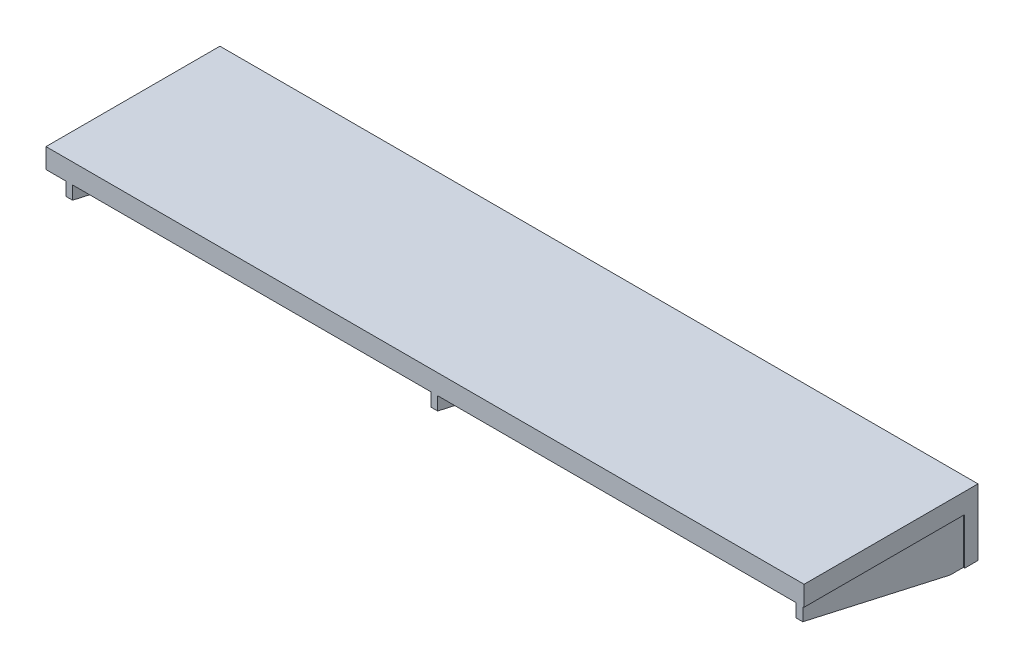
SolidWorks part; units mm, degrees
ref_plane "前视基准面" through (0, 0, 0) normal (0, 0, 1) x (1, 0, 0)
ref_plane "上视基准面" through (0, 0, 0) normal (0, 1, 0) x (1, 0, 0)
ref_plane "右视基准面" through (0, 0, 0) normal (1, 0, 0) x (0, 0, -1)
sketch "草图1" plane through (0, 0, 0) normal (0, 0, 1) x (1, 0, 0)
  line L1 (-571, -50) -> (571, -50)
  line L2 (-571, -50) -> (-571, 50)
  line L3 (-571, 50) -> (571, 50)
  line L4 (571, -50) -> (571, 50)
  line L5 (-571, -50) -> (571, 50) construction
  line L6 (-571, 50) -> (571, -50) construction
  point P0 (0, 0)
  dimension "D1" = 1142
  dimension "D2" = 100
extrude "凸台-拉伸1" add sketch "草图1" along normal blind 20
sketch "草图2" plane through (0, 0, 20) normal (0, 0, 1) x (1, 0, 0)
  line L0 (571, -50) -> (571, 50) construction
  line L1 (-571, 50) -> (571, 50)
  line L2 (-571, 50) -> (-571, 20)
  line L3 (-571, 20) -> (571, 20)
  line L4 (571, 50) -> (571, 20)
  dimension "D1" = 30
extrude "凸台-拉伸2" add sketch "草图2" along normal blind 242 separate body
sketch "草图3" plane through (-571, 0, 0) normal (-1, 0, 0) x (0, 0, 1)
  line L0 (262, 20) -> (20, 20)
  line L1 (20, 20) -> (20, -50)
  line L2 (20, -50) -> (40, -50)
  line L3 (40, -50) -> (262, 0)
  line L4 (262, 0) -> (262, 20)
  dimension "D1" = 20
  dimension "D2" = 20
extrude "凸台-拉伸3" add sketch "草图3" against normal blind 10 from offset 30 offset against normal yes
pattern_linear "阵列(线性)1" count 3 spacing 550 along (1, 0, 0) of "凸台-拉伸3"
sketch "草图4" plane through (0, 50, 0) normal (0, 1, 0) x (1, 0, 0)
  line L0 (-571, -262) -> (-571, 0) construction
  line L1 (571, -262) -> (-571, -262)
  line L2 (571, -262) -> (571, -162)
  line L3 (571, -162) -> (-571, -162)
  line L4 (-571, -262) -> (-571, -162)
  dimension "D1" = 100
extrude "凸台-拉伸4" [suppressed] add sketch "草图4" along normal blind 20 separate body
